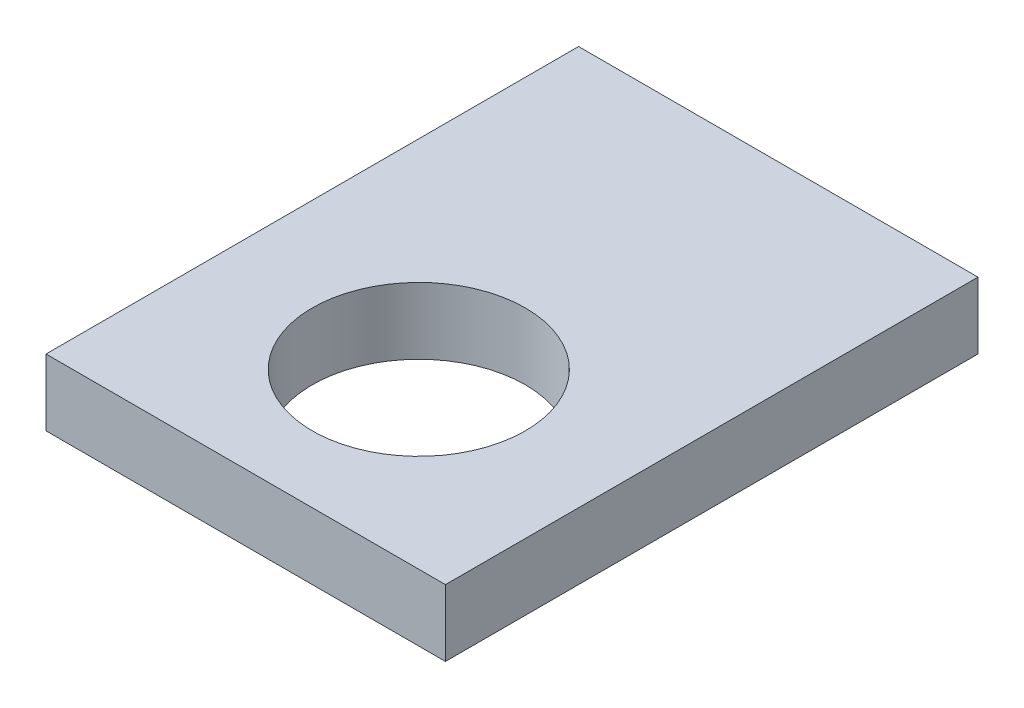
SolidWorks part; units mm, degrees
ref_plane "Plan de face" through (0, 0, 0) normal (0, 0, 1) x (1, 0, 0)
ref_plane "Plan de dessus" through (0, 0, 0) normal (0, 1, 0) x (1, 0, 0)
ref_plane "Plan de droite" through (0, 0, 0) normal (1, 0, 0) x (0, 0, -1)
sketch "Esquisse1" plane through (0, 0, 0) normal (0, 0, 1) x (1, 0, 0)
  line L1 (0, 0) -> (30, 0)
  line L2 (0, 0) -> (0, 5)
  line L3 (0, 5) -> (30, 5)
  line L4 (30, 0) -> (30, 5)
  dimension "D1" = 30
  dimension "D2" = 5
extrude "Boss.-Extru.1" add sketch "Esquisse1" along normal blind 40
sketch "Esquisse2" plane through (0, 0, 0) normal (0, -1, 0) x (1, 0, 0)
  line L0 (15, 40) -> (15, 0) construction
  line L1 (0, 40) -> (30, 40) construction
  line L2 (0, 0) -> (30, 0) construction
  circle A0 centre (15, 27) radius 8
  point P8 (15, 29.8846)
  dimension "D1" = 16
  dimension "D2" = 13
extrude "Enlèv. mat.-Extru.1" cut sketch "Esquisse2" against normal through all
